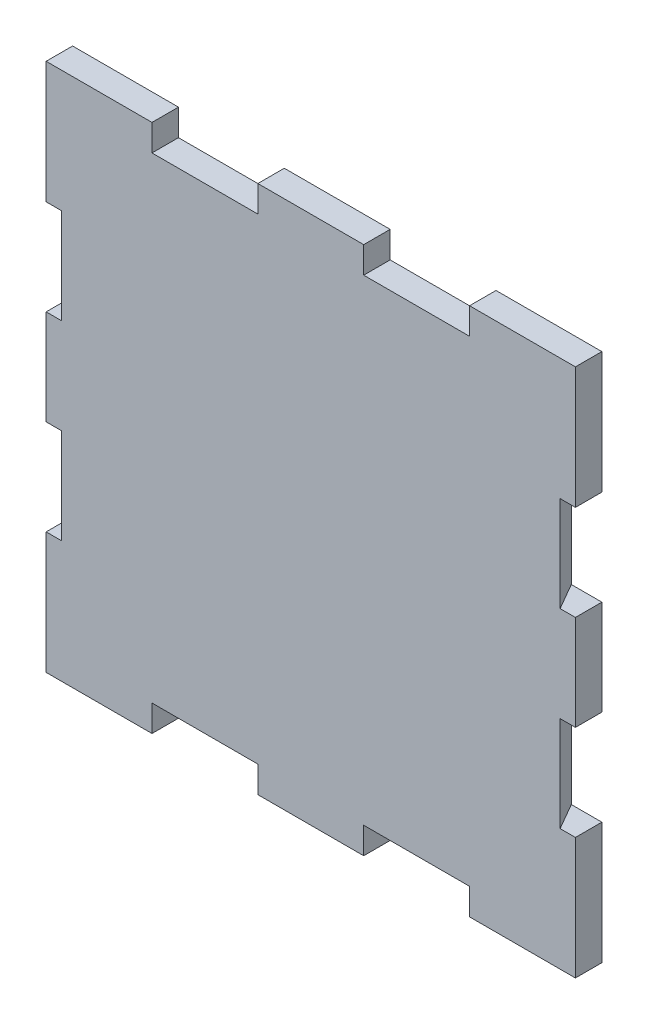
SolidWorks part; units mm, degrees
ref_plane "Front Plane" through (0, 0, 0) normal (0, 0, 1) x (1, 0, 0)
ref_plane "Top Plane" through (0, 0, 0) normal (0, 1, 0) x (1, 0, 0)
ref_plane "Right Plane" through (0, 0, 0) normal (1, 0, 0) x (0, 0, -1)
sketch "Esquisse1" plane through (0, 0, 0) normal (0, 0, 1) x (1, 0, 0)
  line L1 (0, 0) -> (-100, 0)
  line L2 (0, 0) -> (0, -100)
  line L3 (0, -100) -> (-100, -100)
  line L4 (-100, 0) -> (-100, -100)
  line L5 (-50, -100) -> (-50, 0) construction
  line L6 (0, -50) -> (-100, -50) construction
  point P96 (-50, -50)
  dimension "D1" = 100
extrude "Boss.-Extru.1" add sketch "Esquisse1" along normal blind 5
sketch "Esquisse2" plane through (0, 0, 5) normal (0, 0, 1) x (1, 0, 0)
  line L0 (0, 0) -> (-100, 0) construction
  line L1 (-80, -5) -> (-60, -5)
  line L2 (-80, -5) -> (-80, 0)
  line L3 (-80, 0) -> (-60, 0)
  line L4 (-60, -5) -> (-60, 0)
  line L5 (-70, 0) -> (-70, -5) construction
  line L6 (-80, -2.5) -> (-60, -2.5) construction
  line L7 (-60, 0) -> (-60, -5) construction
  line L8 (-20, 0) -> (-20, -5) construction
  line L9 (-40, -5) -> (-20, -5)
  line L10 (-40, -5) -> (-40, 0)
  line L11 (-40, 0) -> (-20, 0)
  line L12 (-20, -5) -> (-20, 0)
  line L13 (-30, 0) -> (-30, -5) construction
  line L14 (-40, -2.5) -> (-20, -2.5) construction
  line L15 (-100, -50) -> (0, -50) construction
  line L16 (-100, 0) -> (-100, -100) construction
  line L17 (0, -100) -> (0, 0) construction
  line L18 (-40, -97.5) -> (-20, -97.5) construction
  line L19 (-30, -100) -> (-30, -95) construction
  line L20 (-80, -97.5) -> (-60, -97.5) construction
  line L21 (-70, -100) -> (-70, -95) construction
  line L22 (-20, -95) -> (-20, -100)
  line L23 (-40, -100) -> (-20, -100)
  line L24 (-40, -95) -> (-40, -100)
  line L25 (-40, -95) -> (-20, -95)
  line L26 (-60, -95) -> (-60, -100)
  line L27 (-80, -100) -> (-60, -100)
  line L28 (-80, -95) -> (-80, -100)
  line L29 (-80, -95) -> (-60, -95)
  point P40 (-70, -97.5)
  point P41 (-30, -97.5)
  point P126 (-30, -2.5)
  point P380 (-70, -2.5)
extrude "Enlèv. mat.-Extru.1" cut sketch "Esquisse2" against normal through all
sketch "Esquisse3" plane through (0, 0, 5) normal (0, 0, 1) x (1, 0, 0)
  line L0 (-100, 0) -> (-100, -100) construction
  line L1 (-97.1132, -23) -> (-100, -23)
  line L2 (-97.1132, -23) -> (-97.1132, -41)
  line L3 (-97.1132, -41) -> (-100, -41)
  line L4 (-100, -23) -> (-100, -41)
  line L5 (-98.5566, -41) -> (-98.5566, -23) construction
  line L6 (-97.1132, -32) -> (-100, -32) construction
  line L7 (-100, -41) -> (-97.1132, -41) construction
  line L8 (-100, -77) -> (-97.1132, -77) construction
  line L9 (-97.1132, -59) -> (-100, -59)
  line L10 (-97.1132, -59) -> (-97.1132, -77)
  line L11 (-97.1132, -77) -> (-100, -77)
  line L12 (-100, -59) -> (-100, -77)
  line L13 (-98.5566, -77) -> (-98.5566, -59) construction
  line L14 (-97.1132, -68) -> (-100, -68) construction
  line L15 (-50, 0) -> (-50, -100) construction
  line L16 (-40, 0) -> (-60, 0) construction
  line L17 (-60, -100) -> (-40, -100) construction
  line L18 (-2.8868, -68) -> (0, -68) construction
  line L19 (-1.4434, -77) -> (-1.4434, -59) construction
  line L20 (-2.8868, -32) -> (0, -32) construction
  line L21 (-1.4434, -41) -> (-1.4434, -23) construction
  line L22 (0, -59) -> (0, -77)
  line L23 (-2.8868, -77) -> (0, -77)
  line L24 (-2.8868, -59) -> (-2.8868, -77)
  line L25 (-2.8868, -59) -> (0, -59)
  line L26 (0, -23) -> (0, -41)
  line L27 (-2.8868, -41) -> (0, -41)
  line L28 (-2.8868, -23) -> (-2.8868, -41)
  line L29 (-2.8868, -23) -> (0, -23)
  point P40 (-1.4434, -32)
  point P41 (-1.4434, -68)
  point P122 (-98.5566, -68)
  point P320 (-98.5566, -32)
extrude "Enlèv. mat.-Extru.2" cut sketch "Esquisse3" against normal through all
sketch "Esquisse5" plane through (0, -59, 0) normal (0, -1, 0) x (1, 0, 0)
  line L0 (-97.1132, 0) -> (-97.1132, 5)
  line L1 (-97.1132, 5) -> (-94.2265, 0)
  line L2 (-100, 0) -> (-80, 0) construction
  line L3 (-94.2265, 0) -> (-85.6699, -14.8205) construction
  line L4 (-94.2265, 0) -> (-97.1132, 0)
extrude "Enlèv. mat.-Extru.5" cut sketch "Esquisse5" along normal up to surface (18 mm away) up to face at (-98.5566, -77, 2.5)
sketch "Esquisse6" plane through (0, -41, 0) normal (0, 1, 0) x (1, 0, 0)
  line L3 (-97.1132, 0) -> (-97.1132, -5)
  line L4 (-97.1132, -5) -> (-94.2265, 0)
  line L5 (-94.2265, 0) -> (-97.1132, 0)
  line L6 (-97.1132, 0) -> (-97.1132, -5)
  line L7 (-97.1132, -5) -> (-94.2265, 0)
  line L8 (-94.2265, 0) -> (-97.1132, 0)
  dimension "D1" = 0
extrude "Enlèv. mat.-Extru.6" cut sketch "Esquisse6" along normal up to surface (18 mm away) up to face at (-98.5566, -23, 2.5)
sketch "Esquisse7" plane through (0, -59, 0) normal (0, -1, 0) x (1, 0, 0)
  line L0 (-2.8868, 0) -> (-2.8868, 5)
  line L1 (-2.8868, 5) -> (-5.7735, 0)
  line L2 (-20, 0) -> (0, 0) construction
  line L3 (-5.7735, 0) -> (-14.3301, -14.8205) construction
  line L4 (-5.7735, 0) -> (-2.8868, 0)
extrude "Enlèv. mat.-Extru.7" cut sketch "Esquisse7" along normal up to surface (18 mm away) up to face at (-1.4434, -77, 2.5)
sketch "Esquisse8" plane through (0, -23, 0) normal (0, -1, 0) x (1, 0, 0)
  line L3 (-2.8868, 0) -> (-2.8868, 5)
  line L4 (-2.8868, 5) -> (-5.7735, 0)
  line L5 (-5.7735, 0) -> (-2.8868, 0)
  line L6 (-2.8868, 0) -> (-2.8868, 5)
  line L7 (-2.8868, 5) -> (-5.7735, 0)
  line L8 (-5.7735, 0) -> (-2.8868, 0)
  dimension "D1" = 0
extrude "Enlèv. mat.-Extru.8" cut sketch "Esquisse8" along normal up to surface (18 mm away) up to face at (-1.4434, -41, 2.5)
